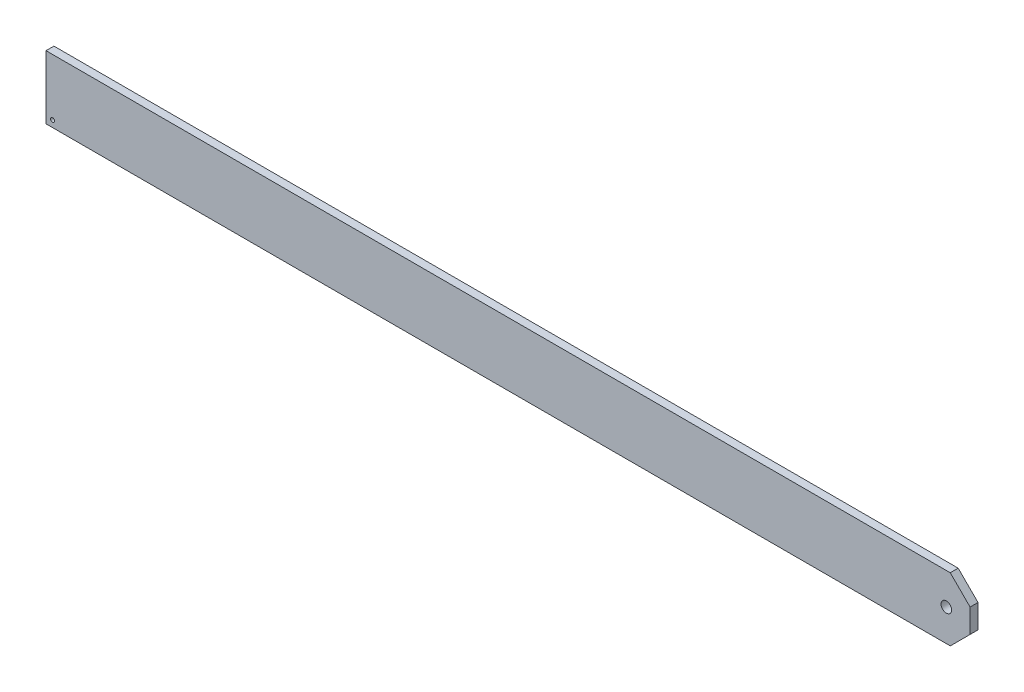
SolidWorks part; units mm, degrees
material "Acrylic (Medium-high impact)"
ref_plane "Front Plane" through (0, 0, 0) normal (0, 0, 1) x (1, 0, 0)
ref_plane "Top Plane" through (0, 0, 0) normal (0, 1, 0) x (1, 0, 0)
ref_plane "Right Plane" through (0, 0, 0) normal (1, 0, 0) x (0, 0, -1)
sketch "Sketch1" plane through (0, 0, 0) normal (0, 0, 1) x (1, 0, 0)
  line L0 (377.5843, 60.1348) -> (392.5843, 45.1348)
  line L1 (-307.4157, 60.1348) -> (377.5843, 60.1348)
  line L2 (-307.4157, 60.1348) -> (-307.4157, 12.1348)
  line L3 (-307.4157, 12.1348) -> (377.5843, 12.1348)
  line L4 (392.5843, 45.1348) -> (392.5843, 27.1348)
  line L5 (377.5843, 12.1348) -> (392.5843, 27.1348)
  line L6 (392.5843, 36.1348) -> (309.5156, 36.1348) construction
  circle A0 centre (374.5843, 36.1348) radius 4
  point P1 (392.5843, 12.1348)
  point P3 (392.5843, 60.1348)
  point P12 (356.7679, 60.1348)
  dimension "D3" = 8
  dimension "D1" = 48
  dimension "D2" = 700
  dimension "D4" = 18
  dimension "D5" = 664.1836
extrude "Boss-Extrude1" add sketch "Sketch1" along normal blind 6
sketch "Sketch2" plane through (0, 0, 6) normal (0, 0, 1) x (1, 0, 0)
  line L0 (-307.4157, 12.1348) -> (-288.3059, 31.2447) construction
  line L1 (-307.4157, 12.1348) -> (377.5843, 12.1348) construction
  line L2 (-307.4157, 60.1348) -> (-307.4157, 12.1348) construction
  circle A0 centre (-302.4157, 17.1348) radius 1.5
  dimension "D2" = 3
  dimension "D1" = 45
  dimension "D3" = 5
extrude "Cut-Extrude1" cut sketch "Sketch2" against normal blind 10
